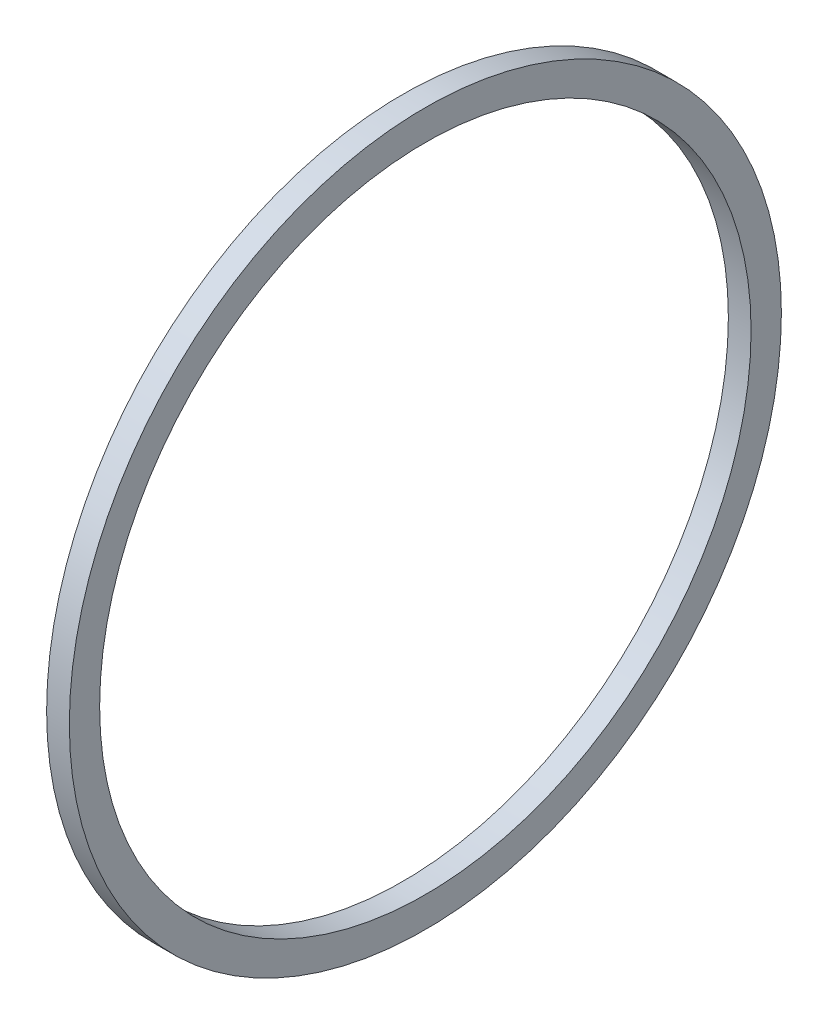
SolidWorks part; units mm, degrees
ref_plane "Front Plane" through (0, 0, 0) normal (0, 0, 1) x (1, 0, 0)
ref_plane "Top Plane" through (0, 0, 0) normal (0, 1, 0) x (1, 0, 0)
ref_plane "Right Plane" through (0, 0, 0) normal (1, 0, 0) x (0, 0, -1)
sketch "Sketch1" plane through (0, 0, 0) normal (1, 0, 0) x (0, 0, -1)
  circle A0 centre (0, 0) radius 43
  circle A1 centre (0, 0) radius 47
  dimension "D1" = 86
  dimension "D2" = 94
extrude "Boss-Extrude1" add sketch "Sketch1" along normal blind 3
